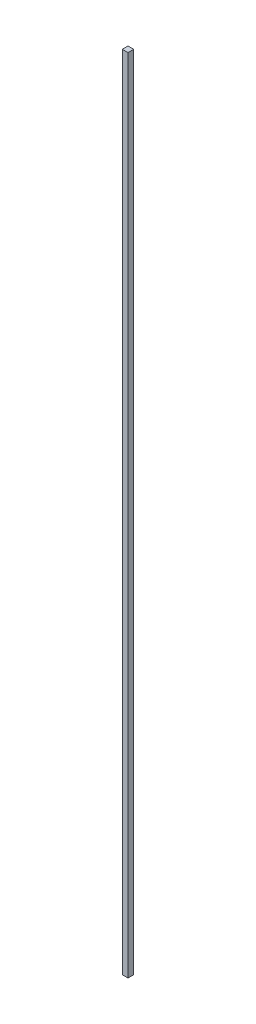
SolidWorks part; units mm, degrees
ref_plane "Front Plane" through (0, 0, 0) normal (0, 0, 1) x (1, 0, 0)
ref_plane "Top Plane" through (0, 0, 0) normal (0, 1, 0) x (1, 0, 0)
ref_plane "Right Plane" through (0, 0, 0) normal (1, 0, 0) x (0, 0, -1)
sketch "Sketch2" plane through (0, 0, 0) normal (0, 1, 0) x (1, 0, 0)
  line L1 (-0.25, 0.25) -> (0.25, 0.25)
  line L2 (-0.25, 0.25) -> (-0.25, -0.25)
  line L3 (-0.25, -0.25) -> (0.25, -0.25)
  line L4 (0.25, 0.25) -> (0.25, -0.25)
  line L5 (-0.25, 0.25) -> (0.25, -0.25) construction
  line L6 (-0.25, -0.25) -> (0.25, 0.25) construction
  point P0 (0, 0)
  dimension "D1" = 0.5
  dimension "D2" = 0.5
extrude "Boss-Extrude2" add sketch "Sketch2" along normal blind 70
